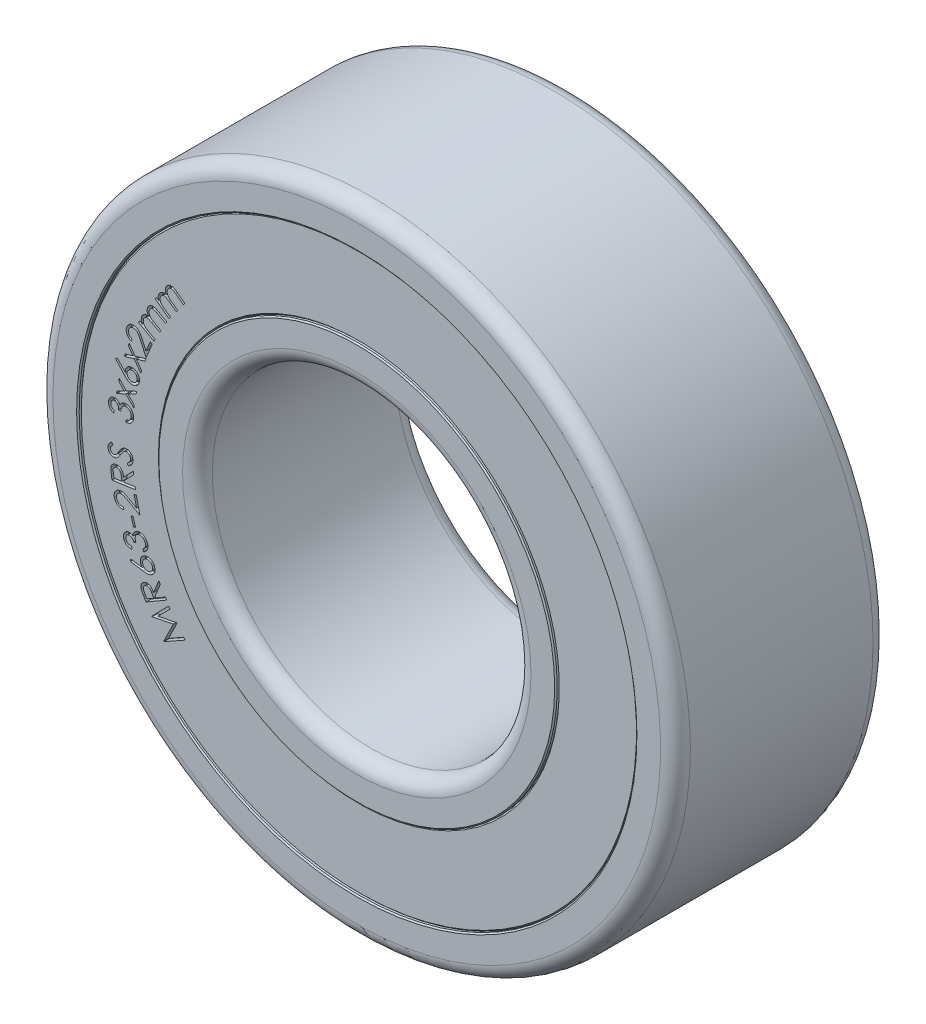
SolidWorks part; units mm, degrees
material "AISI 316 Annealed Stainless Steel Bar (SS)"
ref_plane "Front" through (0, 0, 0) normal (0, 0, 1) x (1, 0, 0)
ref_plane "Top" through (0, 0, 0) normal (0, 1, 0) x (1, 0, 0)
ref_plane "Right" through (0, 0, 0) normal (1, 0, 0) x (0, 0, -1)
sketch "LAYOUT R" plane through (0, 0, 0) normal (1, 0, 0) x (0, 0, -1)
  line L0 (-1, 1.5) -> (1, 1.5)
  line L1 (1, -3) -> (-1, -3) construction
  line L2 (1, -3) -> (1, 3) construction
  line L3 (1, 3) -> (-1, 3)
  line L4 (-1, -3) -> (-1, 3) construction
  line L5 (1, -3) -> (-1, 3) construction
  line L6 (1, 3) -> (-1, -3) construction
  line L7 (-1, 1.875) -> (1, 1.875)
  line L8 (-1, 2.625) -> (1, 2.625)
  line L11 (-17.5, 0) -> (17.5, 0) construction
  line L12 (-1, 3) -> (-1, 2.625)
  line L13 (1, 3) -> (1, 2.625)
  line L14 (-1, 2.625) -> (-1, 1.875)
  line L15 (1, 2.625) -> (1, 1.875)
  line L16 (-1, 1.875) -> (-1, 1.5)
  line L17 (1, 1.875) -> (1, 1.5)
  line L18 (-0.98, 2.625) -> (-0.98, 1.875)
  line L19 (0.98, 2.625) -> (0.98, 1.875)
  point P0 (0, 0)
  point P15 (0, 0)
  dimension "D1" = 2
  dimension "D2" = 6
  dimension "D3" = 1.5
  dimension "D6" = 0.02
  dimension "D7" = 0.02
  dimension "D4" = 1.875
  dimension "D5" = 2.625
sketch "Sketch R, INNER BODY" plane through (0, 0, 0) normal (1, 0, 0) x (0, 0, -1)
  line L0 (-1, 1.5) -> (1, 1.5) construction
  line L2 (-1, 1.875) -> (1, 1.875) construction
  line L4 (-1, 1.5) -> (1, 1.5)
  line L6 (-1, 1.875) -> (1, 1.875)
  line L8 (1, 1.875) -> (1, 1.5) construction
  line L9 (-1, 1.875) -> (-1, 1.5) construction
  line L10 (1, 1.875) -> (1, 1.5)
  line L11 (-1, 1.875) -> (-1, 1.5)
  line L12 (-17.5, 0) -> (17.5, 0) construction
  line L13 (-17.5, 0) -> (17.5, 0) construction
sketch "Sketch R, OUTER BODY" plane through (0, 0, 0) normal (1, 0, 0) x (0, 0, -1)
  line L2 (-1, 2.625) -> (1, 2.625) construction
  line L3 (1, 3) -> (-1, 3) construction
  line L6 (-1, 2.625) -> (1, 2.625)
  line L7 (1, 3) -> (-1, 3)
  line L8 (-17.5, 0) -> (17.5, 0) construction
  line L9 (-17.5, 0) -> (17.5, 0) construction
  line L10 (1, 3) -> (1, 2.625) construction
  line L11 (-1, 3) -> (-1, 2.625) construction
  line L12 (1, 3) -> (1, 2.625)
  line L13 (-1, 3) -> (-1, 2.625)
sketch "Sketch R, SEAL FACES" plane through (0, 0, 0) normal (1, 0, 0) x (0, 0, -1)
  line L0 (-17.5, 0) -> (17.5, 0) construction
  line L1 (-17.5, 0) -> (17.5, 0) construction
  line L3 (-1, 1.875) -> (1, 1.875) construction
  line L5 (-1, 2.625) -> (1, 2.625) construction
  line L7 (-0.98, 1.875) -> (0.98, 1.875)
  line L9 (-0.98, 2.625) -> (0.98, 2.625)
  line L10 (0.98, 2.625) -> (0.98, 1.875) construction
  line L11 (-0.98, 2.625) -> (-0.98, 1.875) construction
  line L12 (0.98, 2.625) -> (0.98, 1.875)
  line L13 (-0.98, 2.625) -> (-0.98, 1.875)
revolve "Revolve INNER BODY" add sketch "Sketch R, INNER BODY" angle 360 about L13
fillet "Fillet INNER BODY" radius 0.14 2 edges at (1.5, 0, 1) (1.5, 0, -1)
chamfer "Chamfer INNER BODY" distance 0.012 angle 45 2 edges at (1.875, 0, -1) (1.875, 0, 1)
revolve "Revolve OUTER BODY" add sketch "Sketch R, OUTER BODY" angle 360 about L9
fillet "Fillet OUTER BODY" radius 0.14 2 edges at (3, 0, -1) (3, 0, 1)
chamfer "Chamfer OUTER BODY" distance 0.012 angle 45 2 edges at (2.625, 0, 1) (2.625, 0, -1)
revolve "Revolve SEALS" add sketch "Sketch R, SEAL FACES" angle 360 about L1
chamfer "Chamfer SEALS" distance 0.012 angle 45 4 edges at (1.875, 0, -0.98) (2.625, 0, -0.98) (2.625, 0, 0.98) (1.875, 0, 0.98)
sketch "Sketch TEXT RADIUS 1 — MANUALLY ASSIGN TEXT AND FONT SIZE (FROM EQUATIONS)" plane through (0, 0, 0.98) normal (0, 0, 1) x (1, 0, 0)
  circle A0 centre (0, 0) radius 2.1375 construction
  text T0 "MR63-2RS  3x6x2mm" font "Century Gothic" height 0.225
  dimension "D1" = 4.275
extrude "Cut-Extrude SEAL LABEL 1" cut sketch "Sketch TEXT RADIUS 1 — MANUALLY ASSIGN TEXT AND FONT SIZE (FROM EQUATIONS)" against normal blind 0.05
sketch "Sketch TEXT RADIUS 2 — MANUALLY ASSIGN TEXT AND FONT SIZE (FROM EQUATIONS)" plane through (0, 0, -0.98) normal (0, 0, -1) x (-1, 0, 0)
  circle A0 centre (0, 0) radius 2.1375 construction
  text T0 "MR63-2RS  3x6x2mm" font "Century Gothic" height 0.225
  dimension "D1" = 4.275
extrude "Cut-Extrude SEAL LABEL 2" cut sketch "Sketch TEXT RADIUS 2 — MANUALLY ASSIGN TEXT AND FONT SIZE (FROM EQUATIONS)" against normal blind 0.05
equation "\"_i__BORE\"= 3"
equation "\"_i__OUTSIDE_DIAMETER\"= 6"
equation "\"_i__WIDTH\"= 2"
equation "\"_i_optional__TEXT_RADIUS_ADJUSTMENT\"= 0"
equation "\"_output__FONT_SIZE_mm\"= \"BODY_SPAN__SEAL__OF_RADIUS\" * \"param__FONT_SIZE_RATIO\"'MANUALLY ASSIGN TO FONT"
equation "\"BODY__HALF_WIDTH\"= \"_i__WIDTH\" / 2"
equation "\"BODY_SPAN___OF_DIAMETER\"= \"_i__OUTSIDE_DIAMETER\" - \"_i__BORE\""
equation "\"BODY_SPAN___OF_RADIUS\"= \"BODY_SPAN___OF_DIAMETER\" / 2"
equation "\"BODY_SPAN__BORE_AND_OD__OF RADIUS\"= ( \"BODY_SPAN___OF_RADIUS\" - \"BODY_SPAN__SEAL__OF_RADIUS\" ) / 2"
equation "\"BODY_SPAN__SEAL__OF_RADIUS\"= \"BODY_SPAN___OF_RADIUS\" * \"param__SEAL_PANEL_SPAN__RATIO_OF_BODY_RADIAN\""
equation "\"BORE__RADIUS\"= \"_i__BORE\" / 2"
equation "\"CORNER_RADII\"= \"_i__WIDTH\" * \"param__CORNER_RADII__ISO_MAX_RATIO_TO_WIDTH\""
equation "\"param__CORNER_RADII__ISO_MAX_RATIO_TO_WIDTH\"= 0.07'WHERE WIDTH IS LESS THAN DIAMETER"
equation "\"param__FONT_SIZE_RATIO\"= 0.3"
equation "\"param__SEAL_FACE_INSET__RATIO_OF_WIDTH\"= .01"
equation "\"param__SEAL_PANEL_SPAN__RATIO_OF_BODY_RADIAN\"= 0.5"
equation "\"param__SIDE_CHAMFERS__RATIO_TO_OD\"= 1 / 500"
equation "\"RING_INNER__OUTSIDE_RADIUS\"= \"BORE__RADIUS\" + \"BODY_SPAN__BORE_AND_OD__OF RADIUS\""
equation "\"RING_OUTER__OUTSIDE_RADIUS\"= ( \"_i__OUTSIDE_DIAMETER\" / 2 ) - \"BODY_SPAN__BORE_AND_OD__OF RADIUS\""
equation "\"SEAL_FACE_INSET\"= \"_i__WIDTH\" * \"param__SEAL_FACE_INSET__RATIO_OF_WIDTH\""
equation "\"SIDE_FACE_AND_SEAL_CHAMFERS\"= \"_i__OUTSIDE_DIAMETER\" * \"param__SIDE_CHAMFERS__RATIO_TO_OD\""
equation "\"TEXT_RADIUS\"= \"_i__BORE\" + ( \"BODY_SPAN___OF_DIAMETER\" / 2 ) - \"_output__FONT_SIZE_mm\" + \"_i_optional__TEXT_RADIUS_ADJUSTMENT\""
equation "\"D1@Chamfer INNER BODY\"=\"SIDE_FACE_AND_SEAL_CHAMFERS\""
equation "\"D1@Chamfer OUTER BODY\"=\"SIDE_FACE_AND_SEAL_CHAMFERS\""
equation "\"D1@Chamfer SEALS\"=\"SIDE_FACE_AND_SEAL_CHAMFERS\""
equation "\"D1@Fillet INNER BODY\"=\"CORNER_RADII\""
equation "\"D1@Fillet OUTER BODY\"=\"CORNER_RADII\""
equation "\"D1@LAYOUT R\"=\"_i__WIDTH\""
equation "\"D1@Sketch TEXT RADIUS 1 — MANUALLY ASSIGN TEXT AND FONT SIZE (FROM EQUATIONS)\" = \"TEXT_RADIUS\""
equation "\"D1@Sketch TEXT RADIUS 2 — MANUALLY ASSIGN TEXT AND FONT SIZE (FROM EQUATIONS)\" = \"TEXT_RADIUS\""
equation "\"D2@LAYOUT R\"=\"_i__OUTSIDE_DIAMETER\""
equation "\"D3@LAYOUT R\"=\"BORE__RADIUS\""
equation "\"D4@LAYOUT R\"=\"RING_INNER__OUTSIDE_RADIUS\""
equation "\"D5@LAYOUT R\"=\"RING_OUTER__OUTSIDE_RADIUS\""
